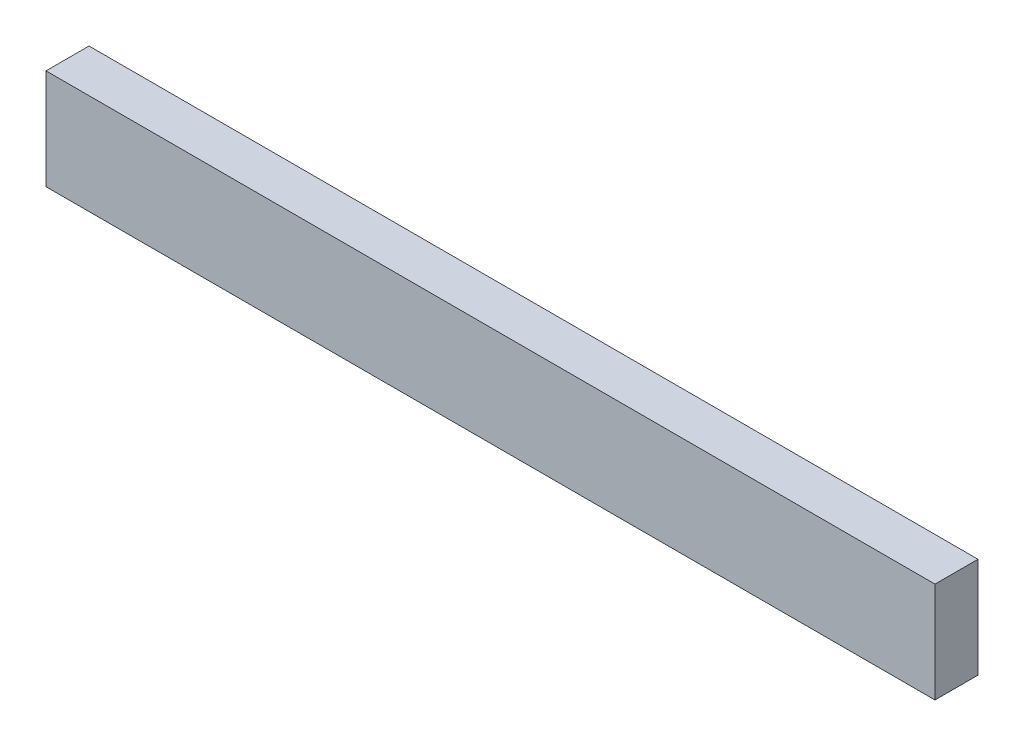
SolidWorks part; units mm, degrees
material "Pine"
ref_plane "Front Plane" through (0, 0, 0) normal (0, 0, 1) x (1, 0, 0)
ref_plane "Top Plane" through (0, 0, 0) normal (0, 1, 0) x (1, 0, 0)
ref_plane "Right Plane" through (0, 0, 0) normal (1, 0, 0) x (0, 0, -1)
sketch "Sketch1" plane through (0, 0, 0) normal (1, 0, 0) x (0, 0, -1)
  line L1 (-19.05, -44.45) -> (19.05, -44.45)
  line L2 (-19.05, -44.45) -> (-19.05, 44.45)
  line L3 (-19.05, 44.45) -> (19.05, 44.45)
  line L4 (19.05, -44.45) -> (19.05, 44.45)
  line L5 (-19.05, -44.45) -> (19.05, 44.45) construction
  line L6 (-19.05, 44.45) -> (19.05, -44.45) construction
  point P0 (0, 0)
  dimension "D1" = 88.9
  dimension "D2" = 38.1
extrude "Boss-Extrude1" add sketch "Sketch1" along normal blind 787.4
